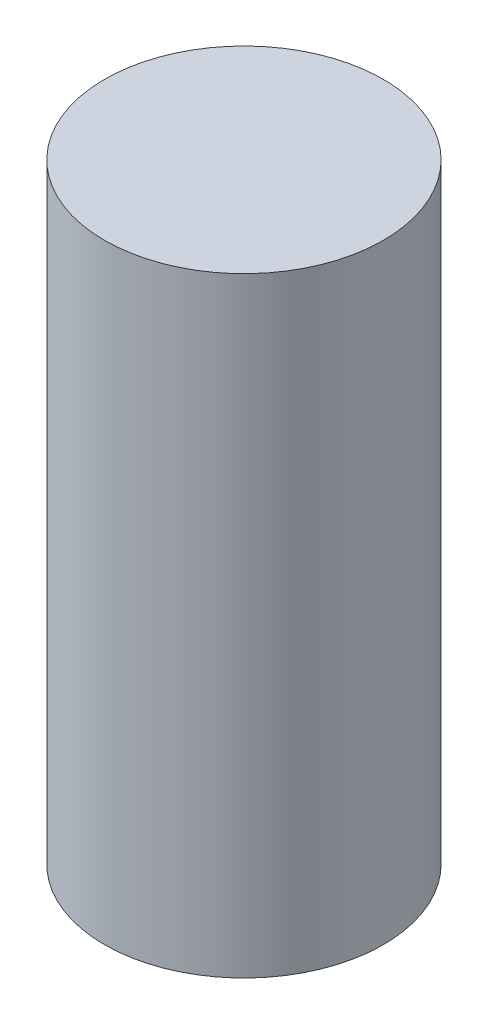
SolidWorks part; units mm, degrees
ref_plane "前视基准面" through (0, 0, 0) normal (0, 0, 1) x (1, 0, 0)
ref_plane "上视基准面" through (0, 0, 0) normal (0, 1, 0) x (1, 0, 0)
ref_plane "右视基准面" through (0, 0, 0) normal (1, 0, 0) x (0, 0, -1)
sketch "草图1" plane through (0, 0, 0) normal (0, 1, 0) x (1, 0, 0)
  circle A1 centre (0, 0) radius 8
  dimension "D2" = 16
extrude "凸台-拉伸1" add sketch "草图1" along normal blind 35
sketch "草图2" plane through (0, 0, 0) normal (0, 0, 1) x (1, 0, 0)
  line L0 (-8, 0) -> (-8, 28)
  line L1 (-8, 35) -> (-8, 0) construction
  line L2 (-8, 28) -> (8, 28)
  line L3 (8, 0) -> (8, 35) construction
  line L4 (8, 28) -> (8, 0)
  line L5 (-8, 0) -> (8, 0) construction
  line L6 (8, 0) -> (-8, 0)
  dimension "D1" = 28
  dimension "D2" = 16
